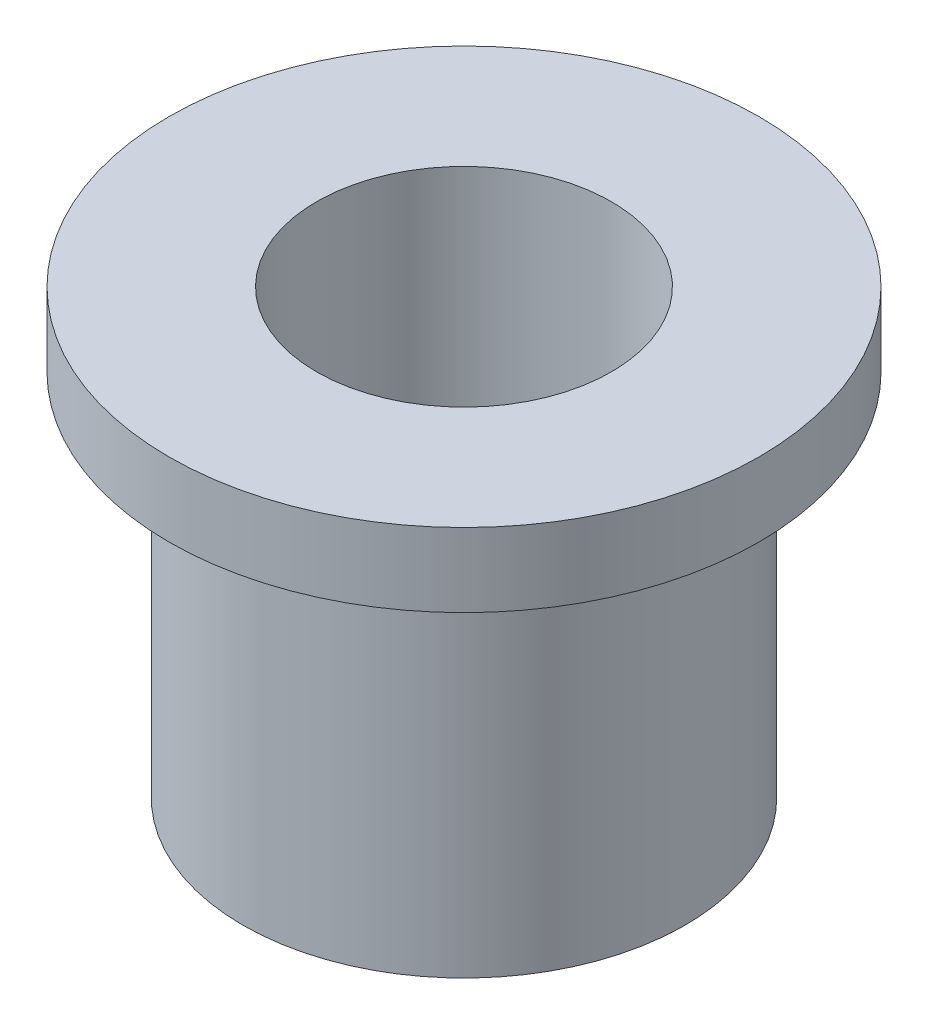
SolidWorks part; units mm, degrees
material "Brass"
ref_plane "Front Plane" through (0, 0, 0) normal (0, 0, 1) x (1, 0, 0)
ref_plane "Top Plane" through (0, 0, 0) normal (0, 1, 0) x (1, 0, 0)
ref_plane "Right Plane" through (0, 0, 0) normal (1, 0, 0) x (0, 0, -1)
sketch "Sketch1" plane through (0, 0, 0) normal (0, 0, 1) x (1, 0, 0)
  line L0 (0, 0) -> (0, -62.7468) construction
  line L1 (3.175, 0) -> (3.175, -9.525)
  line L2 (3.175, -9.525) -> (4.7625, -9.525)
  line L3 (4.7625, -9.525) -> (4.7625, -1.5875)
  line L4 (4.7625, -1.5875) -> (6.35, -1.5875)
  line L5 (6.35, -1.5875) -> (6.35, 0)
  line L6 (6.35, 0) -> (3.175, 0)
  dimension "D1" = 9.525
  dimension "D2" = 6.35
  dimension "D3" = 9.525
  dimension "D4" = 12.7
  dimension "D5" = 1.5875
revolve "Revolve1" add sketch "Sketch1" angle 360 about L0
